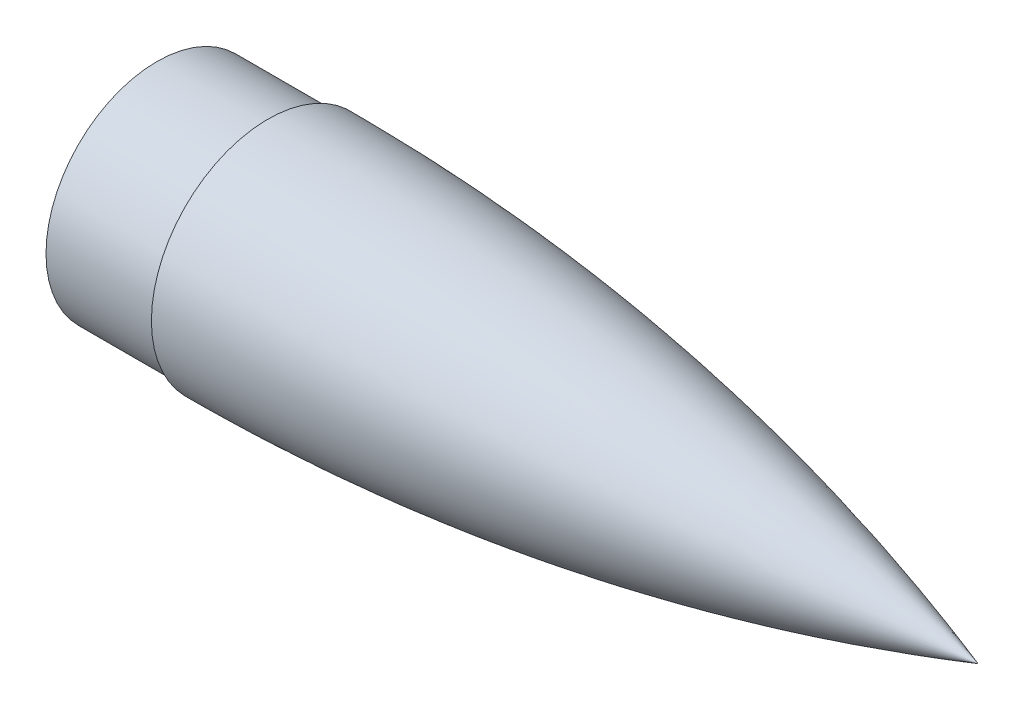
SolidWorks part; units mm, degrees
material "CMR DEFAULT - CHANGE MATERIAL"
ref_plane "XY PLANE - TOP" through (0, 0, 0) normal (0, 0, 1) x (1, 0, 0)
ref_plane "XZ PLANE - SIDE" through (0, 0, 0) normal (0, 1, 0) x (1, 0, 0)
ref_plane "YZ PLANE - FRONT" through (0, 0, 0) normal (1, 0, 0) x (0, 0, -1)
sketch "Sketch2" plane through (0, 0, 0) normal (0, 1, 0) x (1, 0, 0)
  line L0 (63.5, 63.5) -> (0, 63.5)
  line L1 (-55, 0) -> (55, 0) construction
  line L2 (0, 0) -> (0, 63.5) construction
  line L3 (63.5, 63.5) -> (63.5, 66.675)
  line L4 (0, 0) -> (469.9, 0) construction
  line L5 (66.675, 60.325) -> (66.675, 63.496)
  line L6 (66.675, 60.325) -> (0, 60.325)
  line L8 (0, 63.5) -> (0, 60.325)
  line L9 (459.8515, 0) -> (469.9, 0)
  arc A0 (63.5, 66.675) -> (469.9, 0) centre (63.5, -1205.2149) cw
  arc A1 (66.675, 63.496) -> (459.8515, 0) centre (63.5, -1205.2149) cw
  arc A2 (66.675, 63.496) -> (468.8855, -3.0086) centre (63.5, -1205.2149) cw construction
  dimension "D4" = 3.175
  dimension "D1" = 63.5
  dimension "D2" = 63.5
  dimension "D3" = 406.4
  dimension "D5" = 3.175
revolve "Revolve2" add sketch "Sketch2" angle 360 about L4
